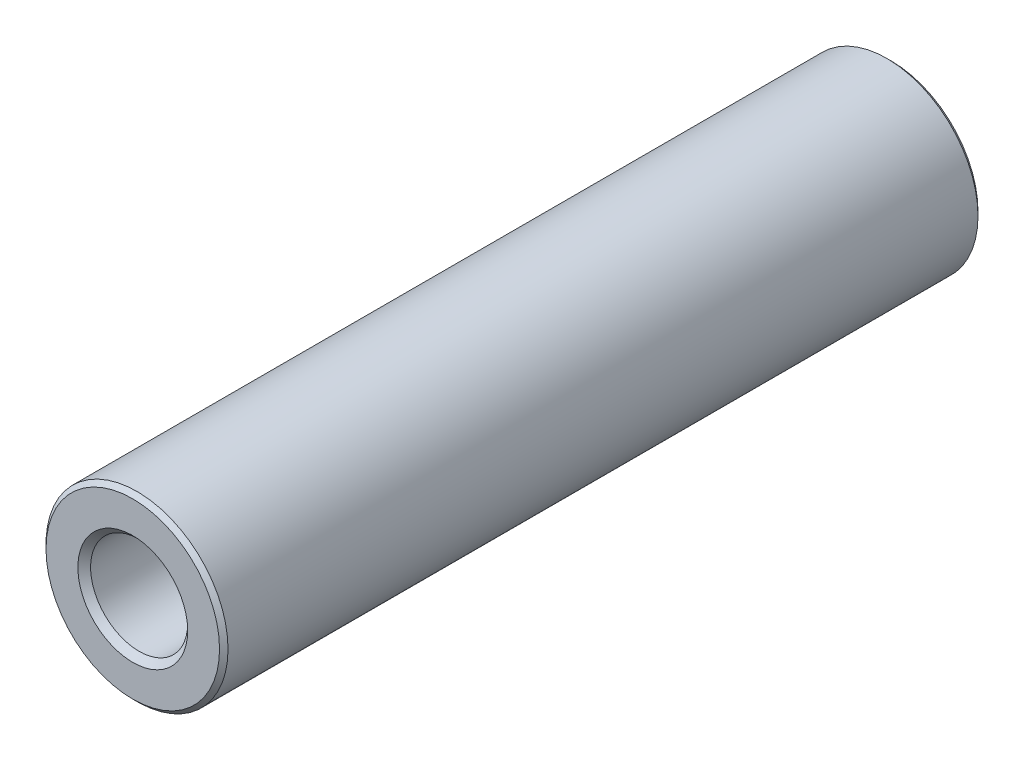
SolidWorks part; units mm, degrees
ref_plane "Front Plane" through (0, 0, 0) normal (0, 0, 1) x (1, 0, 0)
ref_plane "Top Plane" through (0, 0, 0) normal (0, 1, 0) x (1, 0, 0)
ref_plane "Right Plane" through (0, 0, 0) normal (1, 0, 0) x (0, 0, -1)
sketch "Sketch1" plane through (0, 0, 0) normal (0, 0, 1) x (1, 0, 0)
  circle A0 centre (0, 0) radius 3 construction
  circle A1 centre (0, 0) radius 1.6 construction
  point P4 (0, 3)
  dimension "ID" = 3.2
  dimension "OD" = 6
sketch "Sketch2" plane through (0, 0, 0) normal (1, 0, 0) x (0, 0, -1)
  line L0 (-12.5, 3) -> (12.5, 3) construction
  dimension "Length" = 25
sketch "Sketch3" plane through (0, 0, 0) normal (0, 0, 1) x (1, 0, 0)
  circle A0 centre (0, 0) radius 1.6 construction
  circle A1 centre (0, 0) radius 3 construction
  circle A2 centre (0, 0) radius 1.6
  circle A3 centre (0, 0) radius 3
extrude "Boss-Extrude1" add sketch "Sketch3" against normal up to vertex (12.5 mm away) and the other way up to vertex (12.5 mm away) up to point (0, 3, -12.5) other way up to point (0, 3, 12.5)
chamfer "Chamfer1" distance 0.14 angle 45 2 edges at (3, 0, 12.5) (3, 0, -12.5)
chamfer "Chamfer2" distance 0.21 angle 45 2 edges at (1.6, 0, 12.5) (1.6, 0, -12.5)
equation "\"D1@Chamfer1\"=(\"OD@Sketch1\"-\"ID@Sketch1\")*0.05"
equation "\"D1@Chamfer2\"=(\"OD@Sketch1\"-\"ID@Sketch1\")*0.075"
